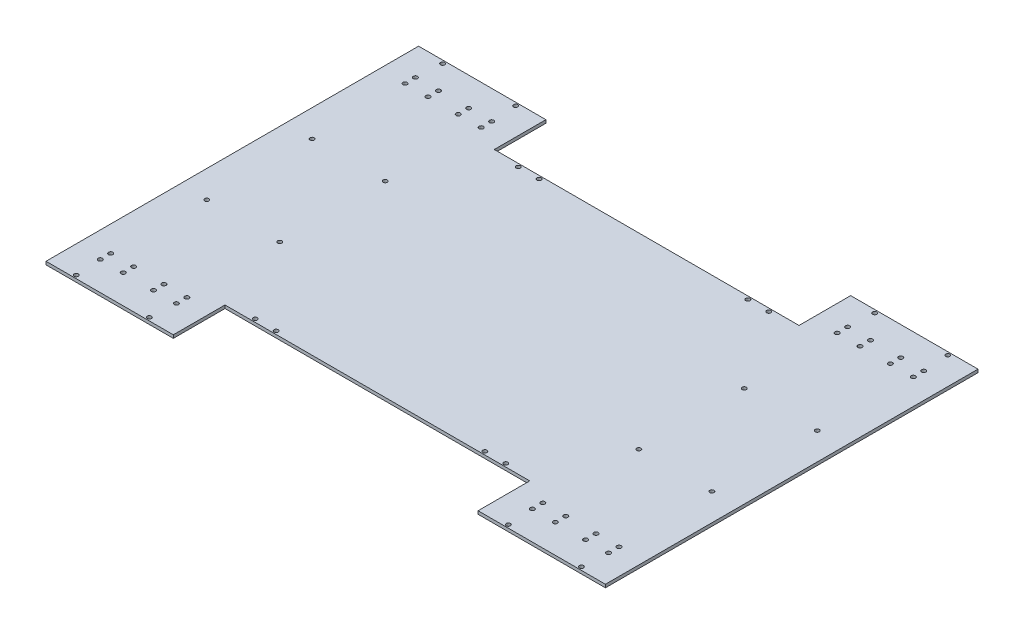
SolidWorks part; units mm, degrees
ref_plane "前视基准面" through (0, 0, 0) normal (0, 0, 1) x (1, 0, 0)
ref_plane "上视基准面" through (0, 0, 0) normal (0, 1, 0) x (1, 0, 0)
ref_plane "右视基准面" through (0, 0, 0) normal (1, 0, 0) x (0, 0, -1)
sketch "草图1" plane through (0, 0, 0) normal (0, 1, 0) x (1, 0, 0)
  line L0 (0, -829) -> (0, 49171) construction
  line L1 (-268, -178.5) -> (268, -178.5)
  line L2 (-268, -178.5) -> (-268, 178.5)
  line L3 (-268, 178.5) -> (268, 178.5)
  line L4 (268, -178.5) -> (268, 178.5)
  line L5 (-268, -178.5) -> (268, 178.5) construction
  line L6 (-268, 178.5) -> (268, -178.5) construction
  line L7 (-1000, 0) -> (49000, 0) construction
  line L25 (146, 178.5) -> (146, 129)
  line L26 (146, 178.5) -> (-146, 178.5)
  line L28 (146, 129) -> (-146, 129)
  line L29 (-146, 178.5) -> (-146, 129)
  line L30 (146, -178.5) -> (146, -129)
  line L31 (146, -178.5) -> (-146, -178.5)
  line L32 (-146, -178.5) -> (-146, -129)
  line L33 (146, -129) -> (-146, -129)
  point P0 (0, 0)
  point P9 (0, 178.5)
  dimension "D1" = 536
  dimension "D2" = 357
  dimension "D3" = 122
  dimension "D4" = 49.5
extrude "凸台-拉伸1" add sketch "草图1" along normal blind 3 contours L33 L30 L1 L4 L3 L25 L28 L29 L2 L32
sketch "草图6" plane through (0, 0, 0) normal (0, -1, 0) x (1, 0, 0)
  line L0 (-848, 0) -> (49152, 0) construction
  line L1 (0, -828.6712) -> (0, 49171.3288) construction
  circle A0 centre (172, 175.5) radius 2
  circle A1 centre (242, 175.5) radius 2
  circle A2 centre (170.5, 151) radius 2.05
  circle A3 centre (192.5, 151) radius 2.05
  circle A4 centre (192.5, 141) radius 2.05
  circle A5 centre (170.5, 141) radius 2.05
  circle A6 centre (221.5, 151) radius 2.05
  circle A7 centre (221.5, 141) radius 2.05
  circle A8 centre (243.5, 151) radius 2.05
  circle A9 centre (243.5, 141) radius 2.05
  circle A10 centre (172, 50.5) radius 2
  circle A11 centre (242, 50.5) radius 2
  circle A12 centre (100, 126) radius 2
  circle A13 centre (120, 126) radius 2
  circle A14 centre (242, -50.5) radius 2
  circle A15 centre (172, -50.5) radius 2
  circle A16 centre (243.5, -141) radius 2.05
  circle A17 centre (243.5, -151) radius 2.05
  circle A18 centre (221.5, -141) radius 2.05
  circle A19 centre (221.5, -151) radius 2.05
  circle A20 centre (192.5, -141) radius 2.05
  circle A21 centre (170.5, -141) radius 2.05
  circle A22 centre (170.5, -151) radius 2.05
  circle A23 centre (192.5, -151) radius 2.05
  circle A24 centre (242, -175.5) radius 2
  circle A25 centre (172, -175.5) radius 2
  circle A26 centre (120, -126) radius 2
  circle A27 centre (100, -126) radius 2
  circle A28 centre (-172, -175.5) radius 2
  circle A29 centre (-242, -175.5) radius 2
  circle A30 centre (-221.5, -151) radius 2.05
  circle A31 centre (-243.5, -151) radius 2.05
  circle A32 centre (-243.5, -141) radius 2.05
  circle A33 centre (-221.5, -141) radius 2.05
  circle A34 centre (-170.5, -151) radius 2.05
  circle A35 centre (-192.5, -151) radius 2.05
  circle A36 centre (-192.5, -141) radius 2.05
  circle A37 centre (-170.5, -141) radius 2.05
  circle A38 centre (-100, -126) radius 2
  circle A39 centre (-120, -126) radius 2
  circle A40 centre (-242, -50.5) radius 2
  circle A41 centre (-172, -50.5) radius 2
  circle A42 centre (-242, 50.5) radius 2
  circle A43 centre (-172, 50.5) radius 2
  circle A44 centre (-243.5, 141) radius 2.05
  circle A45 centre (-243.5, 151) radius 2.05
  circle A46 centre (-221.5, 141) radius 2.05
  circle A47 centre (-221.5, 151) radius 2.05
  circle A48 centre (-192.5, 141) radius 2.05
  circle A49 centre (-170.5, 141) radius 2.05
  circle A50 centre (-192.5, 151) radius 2.05
  circle A51 centre (-170.5, 151) radius 2.05
  circle A52 centre (-242, 175.5) radius 2
  circle A53 centre (-172, 175.5) radius 2
  circle A54 centre (-120, 126) radius 2
  circle A55 centre (-100, 126) radius 2
  dimension "D1" = 101
  dimension "D2" = 101
  dimension "D3" = 252
  dimension "D4" = 252
  dimension "D5" = 200
  dimension "D6" = 240
  dimension "D7" = 351
  dimension "D8" = 351
  dimension "D9" = 22
  dimension "D10" = 10
  dimension "D11" = 22
  dimension "D12" = 10
  dimension "D13" = 29
  dimension "D14" = 10
  dimension "D15" = 22
  dimension "D16" = 22
  dimension "D17" = 10
  dimension "D18" = 282
  dimension "D19" = 70
  dimension "D20" = 1.5
  dimension "D21" = 344
  dimension "D22" = 344
  dimension "D23" = 484
  dimension "D24" = 10
  dimension "D25" = 22
  dimension "D26" = 29
  dimension "D27" = 70
  dimension "D28" = 282
  dimension "D29" = 70
  dimension "D30" = 29
  dimension "D31" = 344
  dimension "D32" = 484
extrude "切除-拉伸2" cut sketch "草图6" against normal blind 3
